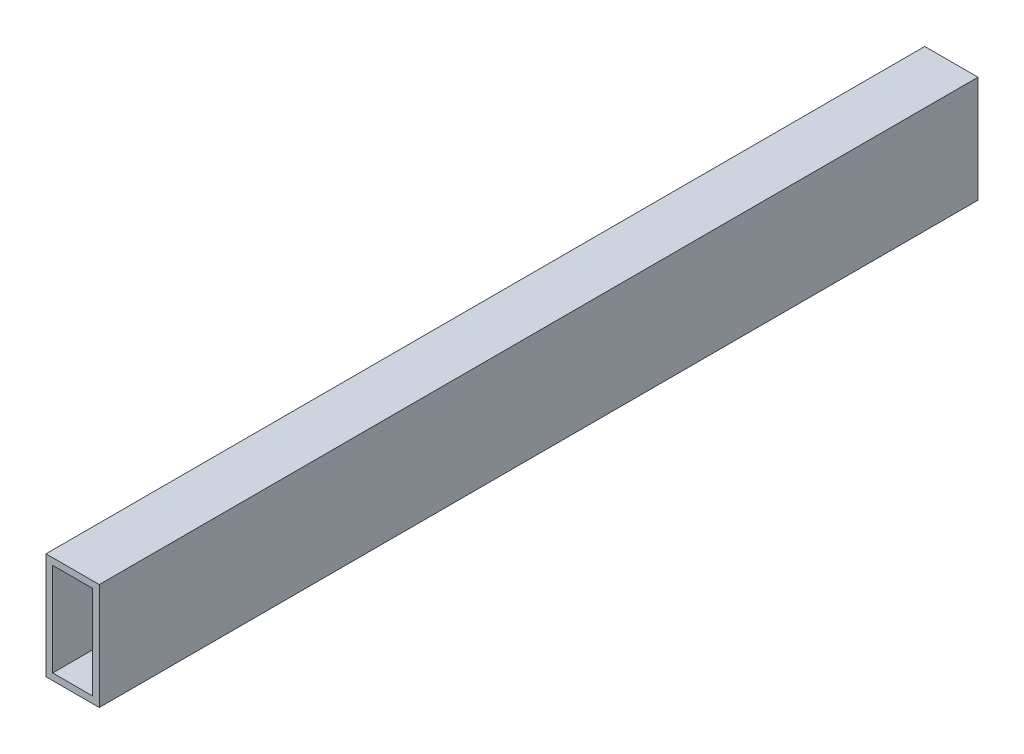
SolidWorks part; units mm, degrees
ref_plane "Front Plane" through (0, 0, 0) normal (0, 0, 1) x (1, 0, 0)
ref_plane "Top Plane" through (0, 0, 0) normal (0, 1, 0) x (1, 0, 0)
ref_plane "Right Plane" through (0, 0, 0) normal (1, 0, 0) x (0, 0, -1)
sketch "Sketch1" plane through (0, 0, 0) normal (0, 0, 1) x (1, 0, 0)
  line L1 (-12.7, 25.4) -> (12.7, 25.4)
  line L2 (-12.7, 25.4) -> (-12.7, -25.4)
  line L3 (-12.7, -25.4) -> (12.7, -25.4)
  line L4 (12.7, 25.4) -> (12.7, -25.4)
  line L5 (-12.7, 25.4) -> (12.7, -25.4) construction
  line L6 (-12.7, -25.4) -> (12.7, 25.4) construction
  line L7 (-9.525, 22.225) -> (9.525, 22.225)
  line L8 (-9.525, 22.225) -> (-9.525, -22.225)
  line L9 (-9.525, -22.225) -> (9.525, -22.225)
  line L10 (9.525, 22.225) -> (9.525, -22.225)
  line L11 (-9.525, 22.225) -> (9.525, -22.225) construction
  line L12 (-9.525, -22.225) -> (9.525, 22.225) construction
  point P0 (0, 0)
  point P5 (0, 0)
  dimension "D1" = 50.8
  dimension "D2" = 25.4
  dimension "D3" = 44.45
  dimension "D4" = 19.05
extrude "Boss-Extrude1" add sketch "Sketch1" along normal blind 419.1
